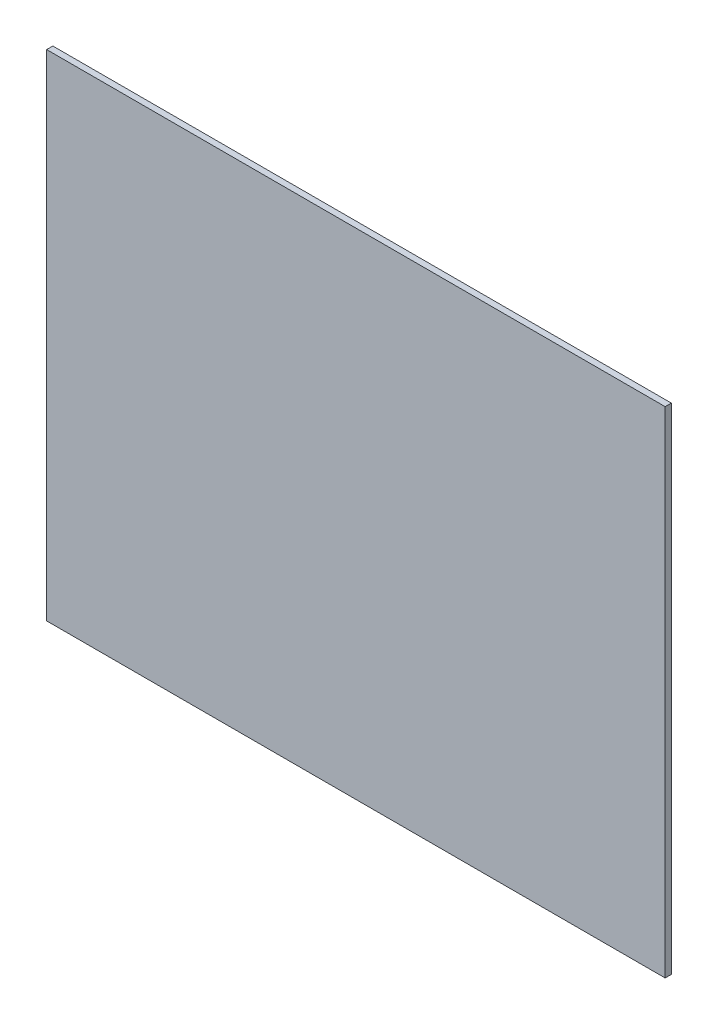
SolidWorks part; units mm, degrees
ref_plane "Plan de face" through (0, 0, 0) normal (0, 0, 1) x (1, 0, 0)
ref_plane "Plan de dessus" through (0, 0, 0) normal (0, 1, 0) x (1, 0, 0)
ref_plane "Plan de droite" through (0, 0, 0) normal (1, 0, 0) x (0, 0, -1)
sketch "Esquisse1" plane through (0, 0, 0) normal (0, 0, 1) x (1, 0, 0)
  line L1 (-439.6357, 251.0163) -> (560.3643, 251.0163)
  line L2 (-439.6357, 251.0163) -> (-439.6357, -548.9837)
  line L3 (-439.6357, -548.9837) -> (560.3643, -548.9837)
  line L4 (560.3643, 251.0163) -> (560.3643, -548.9837)
  dimension "D1" = 1000
  dimension "D2" = 800
extrude "Boss.-Extru.1" add sketch "Esquisse1" along normal blind 10
